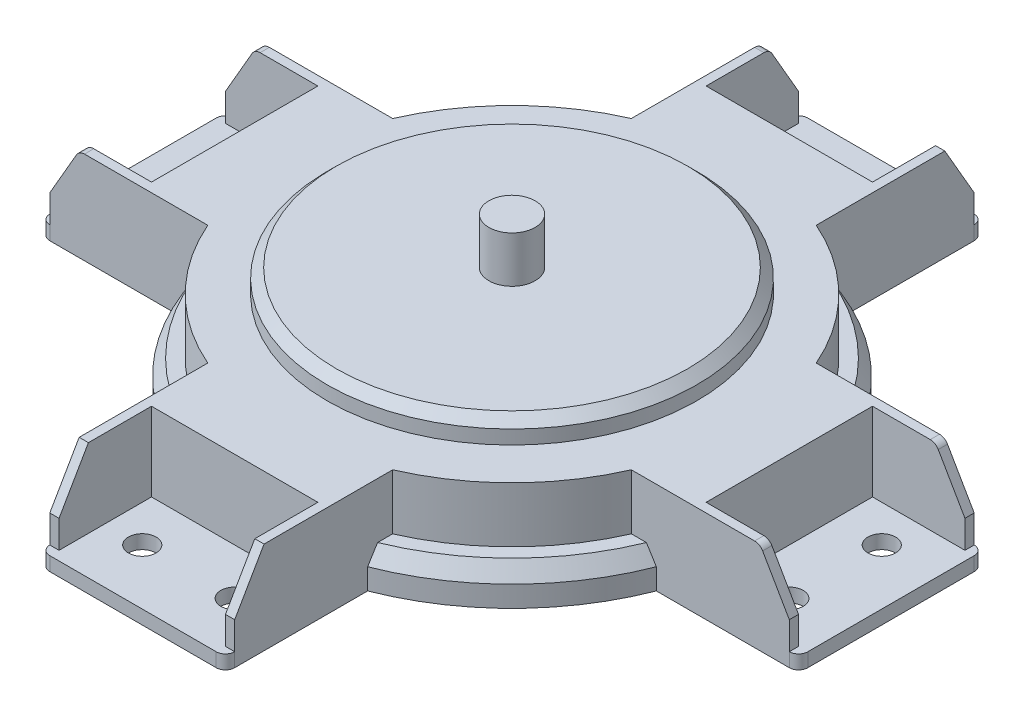
SolidWorks part; units mm, degrees
material "Galvanized Steel"
ref_plane "Front Plane" through (0, 0, 0) normal (0, 0, 1) x (1, 0, 0)
ref_plane "Top Plane" through (0, 0, 0) normal (0, 1, 0) x (1, 0, 0)
ref_plane "Right Plane" through (0, 0, 0) normal (1, 0, 0) x (0, 0, -1)
sketch "Sketch5" plane through (0, 0, 0) normal (0, 1, 0) x (1, 0, 0)
  circle A0 centre (0, 0) radius 250
  dimension "D1" = 500
extrude "Boss-Extrude4" add sketch "Sketch5" along normal blind 100 contours A0
sketch "Sketch6" plane through (0, 100, 0) normal (0, 1, 0) x (1, 0, 0)
  line L0 (0, 0) -> (250, 0)
  line L1 (250, 0) -> (-250, 0)
  line L2 (0, 0) -> (0, 250)
  line L3 (0, 0) -> (0, -250)
  line L11 (-100, -200) -> (-100, -300)
  line L14 (100, -200) -> (100, -300)
  line L15 (100, -300) -> (-100, -300)
  line L16 (100, 200) -> (100, 300)
  line L17 (100, 300) -> (-100, 300)
  line L18 (-100, 200) -> (-100, 300)
  line L19 (200, -100) -> (300, -100)
  line L20 (300, -100) -> (300, 100)
  line L21 (200, 100) -> (300, 100)
  line L22 (-200, -100) -> (-300, -100)
  line L23 (-300, -100) -> (-300, 100)
  line L24 (-200, 100) -> (-300, 100)
  line L25 (-200, 100) -> (-200, -100)
  line L26 (-100, -200) -> (100, -200)
  line L27 (200, -100) -> (200, 100)
  line L28 (100, 200) -> (-100, 200)
  circle A0 centre (0, 0) radius 250 construction
  circle A1 centre (0, 0) radius 4
  circle A2 centre (0, 0) radius 230
  point P6 (0, -123.6494)
  dimension "D1" = 460
  dimension "D5" = 100
  dimension "D7" = 100
  dimension "D8" = 200
sketch "Sketch7" plane through (0, 0, 0) normal (0, 0, 1) x (1, 0, 0)
extrude "Boss-Extrude5" add sketch "Sketch6" against normal blind 100 contours L28 L18 L17 L16 | L25 L22 L23 L24 | L27 L21 L20 L19 | L26 L14 L15 L11
sketch "Sketch10" plane through (0, 0, 0) normal (0, -1, 0) x (1, 0, 0)
  line L0 (-100, 300) -> (-100, 400)
  line L1 (-90, 410) -> (90, 410)
  line L2 (100, 400) -> (100, 300)
  line L3 (100, -310) -> (100, -400)
  line L4 (-100, 300) -> (100, 300)
  line L5 (90, -410) -> (-90, -410)
  line L6 (-100, -400) -> (-100, -300)
  line L7 (-100, -300) -> (90, -300)
  line L8 (-300, -100) -> (-400, -100)
  line L9 (-410, -90) -> (-410, 90)
  line L10 (-400, 100) -> (-300, 100)
  line L11 (-300, 100) -> (-300, -100)
  line L12 (300, -100) -> (400, -100)
  line L13 (410, -90) -> (410, 90)
  line L14 (400, 100) -> (300, 100)
  line L15 (300, 100) -> (300, -100)
  line L16 (90, -300) -> (100, -300)
  line L17 (100, -300) -> (100, -310)
  arc A0 (90, 410) -> (100, 400) centre (90, 400) cw
  arc A1 (-90, 410) -> (-100, 400) centre (-90, 400) ccw
  arc A2 (-100, -400) -> (-90, -410) centre (-90, -400) ccw
  arc A4 (100, -400) -> (90, -410) centre (90, -400) cw
  arc A5 (-410, -90) -> (-400, -100) centre (-400, -90) ccw
  arc A6 (-400, 100) -> (-410, 90) centre (-400, 90) ccw
  arc A7 (410, -90) -> (400, -100) centre (400, -90) cw
  arc A8 (400, 100) -> (410, 90) centre (400, 90) cw
  point P9 (100, 410)
  point P14 (-100, 410)
  point P19 (-100, -410)
  point P22 (100, -300)
  point P25 (100, -410)
  point P34 (-410, -100)
  point P37 (-410, 100)
  point P46 (410, -100)
  point P49 (410, 100)
  dimension "D3" = 10
  dimension "D6" = 10
  dimension "D7" = 10
  dimension "D10" = 10
  dimension "D11" = 10
  dimension "D14" = 10
  dimension "D15" = 10
  dimension "D1" = 110
  dimension "D2" = 200
  dimension "D4" = 110
  dimension "D5" = 200
  dimension "D8" = 110
  dimension "D9" = 200
  dimension "D12" = 110
  dimension "D13" = 200
extrude "Boss-Extrude6" add sketch "Sketch10" against normal blind 15
sketch "Sketch12" plane through (100, 0, 0) normal (1, 0, 0) x (0, 0, -1)
  line L0 (-400, 15) -> (-400, 45)
  line L3 (-300, 15) -> (-300, 100) construction
  line L4 (-400, 15) -> (-300, 15)
  line L5 (-300, 15) -> (-300, 100)
  line L6 (-229.1288, 100) -> (-300, 100) construction
  line L7 (-300, 100) -> (-368.2457, 100)
  line L8 (-400, 45) -> (-368.2457, 100)
  dimension "D1" = 30
extrude "Boss-Extrude7" add sketch "Sketch12" against normal blind 10
sketch "Sketch13" plane through (-100, 0, 0) normal (-1, 0, 0) x (0, 0, 1)
  line L1 (300, 100) -> (300, 15)
  line L4 (300, 15) -> (400, 15)
  line L6 (300, 100) -> (368.2457, 100)
  line L7 (400, 15) -> (400, 45)
  line L8 (400, 45) -> (368.2457, 100)
  point P2 (385.1992, 100)
  dimension "D1" = 30
extrude "Boss-Extrude8" add sketch "Sketch13" against normal blind 10
sketch "Sketch18" plane through (0, 15, 0) normal (0, 1, 0) x (1, 0, 0)
  line L0 (0, -300) -> (0, -350) construction
  line L1 (-90, -300) -> (90, -300) construction
  line L2 (0, -350) -> (-50, -350) construction
  line L3 (-50, -350) -> (50, -350) construction
  line L4 (-300, 0) -> (-350, 0) construction
  line L5 (-300, 100) -> (-300, -100) construction
  line L6 (-350, 0) -> (-350, 50) construction
  line L7 (-350, 50) -> (-350, -50) construction
  line L8 (0, 300) -> (0, 350) construction
  line L9 (100, 300) -> (-100, 300) construction
  line L10 (0, 350) -> (50, 350) construction
  line L11 (50, 350) -> (-50, 350) construction
  line L12 (300, 0) -> (350, 0) construction
  line L13 (300, -100) -> (300, 100) construction
  line L14 (350, 0) -> (350, 50) construction
  line L15 (350, 50) -> (350, -50) construction
  circle A0 centre (-50, -350) radius 15
  circle A1 centre (50, -350) radius 15
  circle A2 centre (-350, 50) radius 15
  circle A3 centre (-350, -50) radius 15
  circle A4 centre (-50, 350) radius 15
  circle A5 centre (50, 350) radius 15
  circle A6 centre (350, 50) radius 15
  circle A7 centre (350, -50) radius 15
  dimension "D4" = 30
  dimension "D5" = 15
  dimension "D9" = 30
  dimension "D10" = 30
  dimension "D12" = 50
  dimension "D14" = 30
  dimension "D15" = 30
  dimension "D19" = 30
  dimension "D20" = 30
  dimension "D1" = 50
  dimension "D2" = 50
  dimension "D3" = 100
  dimension "D6" = 50
  dimension "D7" = 50
  dimension "D8" = 100
  dimension "D11" = 50
  dimension "D13" = 100
  dimension "D16" = 50
  dimension "D17" = 50
  dimension "D18" = 100
extrude "Cut-Extrude2" cut sketch "Sketch18" against normal through all
sketch "Sketch19" plane through (0, 0, 100) normal (0, 0, 1) x (1, 0, 0)
  line L0 (-400, 15) -> (-400, 45)
  line L1 (-400, 45) -> (-371.1325, 95)
  line L2 (-300, 100) -> (-362.4722, 100)
  line L3 (-400, 15) -> (-300, 15)
  line L4 (-300, 15) -> (-300, 100)
  line L5 (400, 15) -> (400, 45)
  line L6 (400, 45) -> (371.1325, 95)
  line L7 (300, 100) -> (362.4722, 100)
  line L8 (300, 100) -> (300, 15)
  line L9 (300, 15) -> (400, 15)
  arc A0 (-371.1325, 95) -> (-362.4722, 100) centre (-362.4722, 90) cw
  arc A1 (371.1325, 95) -> (362.4722, 100) centre (362.4722, 90) ccw
  dimension "D2" = 10
  dimension "D4" = 10
  dimension "D1" = 30
  dimension "D3" = 30
extrude "Boss-Extrude9" add sketch "Sketch19" against normal blind 10
sketch "Sketch20" plane through (0, 0, -100) normal (0, 0, -1) x (-1, 0, 0)
  line L0 (-400, 15) -> (-400, 45)
  line L1 (-400, 45) -> (-371.1325, 95)
  line L2 (-300, 100) -> (-362.4722, 100)
  line L3 (-400, 15) -> (-300, 15)
  line L4 (-300, 15) -> (-300, 100)
  line L5 (400, 15) -> (400, 45)
  line L6 (400, 45) -> (371.1325, 95)
  line L7 (300, 100) -> (362.4722, 100)
  line L8 (300, 100) -> (300, 15)
  line L9 (300, 15) -> (400, 15)
  arc A0 (-362.4722, 100) -> (-371.1325, 95) centre (-362.4722, 90) ccw
  arc A1 (371.1325, 95) -> (362.4722, 100) centre (362.4722, 90) ccw
  dimension "D2" = 10
  dimension "D3" = 10
  dimension "D1" = 30
extrude "Boss-Extrude10" add sketch "Sketch20" against normal blind 10
sketch "Sketch22" plane through (100, 0, 0) normal (1, 0, 0) x (0, 0, -1)
  line L0 (400, 15) -> (400, 45)
  line L1 (400, 45) -> (368.2457, 100)
  line L2 (300, 100) -> (368.2457, 100)
  line L3 (300, 100) -> (300, 15)
  line L4 (300, 15) -> (400, 15)
  dimension "D1" = 30
extrude "Boss-Extrude11" add sketch "Sketch22" against normal blind 10
sketch "Sketch23" plane through (-100, 0, 0) normal (-1, 0, 0) x (0, 0, 1)
  line L0 (-400, 15) -> (-400, 45)
  line L1 (-400, 45) -> (-371.1325, 95)
  line L2 (-300, 100) -> (-362.4722, 100)
  line L3 (-400, 15) -> (-300, 15)
  line L4 (-300, 15) -> (-300, 100)
  arc A0 (-371.1325, 95) -> (-362.4722, 100) centre (-362.4722, 90) cw
  dimension "D2" = 10
  dimension "D1" = 30
extrude "Boss-Extrude12" add sketch "Sketch23" against normal blind 10
sketch "Sketch24" plane through (0, 100, 0) normal (0, 1, 0) x (1, 0, 0)
  circle A0 centre (0, 0) radius 200
  dimension "D1" = 400
extrude "Boss-Extrude13" add sketch "Sketch24" along normal blind 25
sketch "Sketch25" plane through (0, 125, 0) normal (0, 1, 0) x (1, 0, 0)
  circle A0 centre (0, 0) radius 25
  dimension "D1" = 50
extrude "Boss-Extrude14" add sketch "Sketch25" along normal blind 50
sketch "Sketch27" plane through (0, 0, 0) normal (0, -1, 0) x (1, 0, 0)
  line L0 (-256.1738, 100) -> (-229.1288, 100)
  line L1 (-229.1288, 100) -> (-400, 100) construction
  line L2 (-100, 229.1288) -> (-100, 256.1738)
  line L3 (-100, 229.1288) -> (-100, 400) construction
  line L4 (100, 229.1288) -> (100, 400) construction
  line L5 (100, 229.1288) -> (100, 256.1738)
  line L6 (229.1288, 100) -> (256.1738, 100)
  line L7 (100, -256.1738) -> (100, -229.1288)
  line L8 (229.1288, -100) -> (256.1738, -100)
  line L9 (-100, -256.1738) -> (-100, -229.1288)
  line L10 (-256.1738, -100) -> (-229.1288, -100)
  line L12 (-100, -229.1288) -> (-100, -400) construction
  arc A1 (-229.1288, 100) -> (-100, 229.1288) centre (0, 0) cw
  arc A2 (-100, 229.1288) -> (-229.1288, 100) centre (0, 0) ccw construction
  arc A3 (229.1288, 100) -> (100, 229.1288) centre (0, 0) ccw
  arc A4 (229.1288, -100) -> (100, -229.1288) centre (0, 0) cw
  arc A5 (-229.1288, -100) -> (-100, -229.1288) centre (0, 0) ccw
  arc A6 (-256.1738, -100) -> (-100, -256.1738) centre (0, 0) ccw
  arc A7 (-256.1738, 100) -> (-100, 256.1738) centre (0, 0) cw
  arc A8 (100, -256.1738) -> (256.1738, -100) centre (0, 0) ccw
  arc A9 (256.1738, 100) -> (100, 256.1738) centre (0, 0) ccw
extrude "Boss-Extrude15" add sketch "Sketch27" against normal blind 40
chamfer "Chamfer1" distance 10 angle 60 4 edges at (-194.4544, 40, -194.4544) (-194.4544, 40, 194.4544) (194.4544, 40, 194.4544) (194.4544, 40, -194.4544)
chamfer "Chamfer2" distance 10 angle 45 1 edges at (0, 125, 200)
